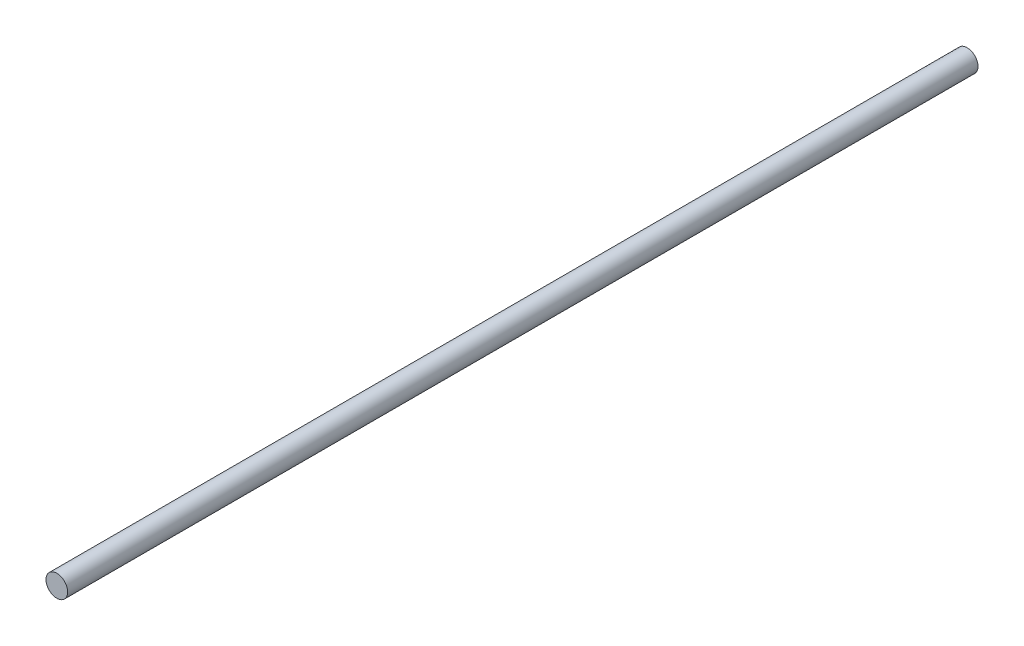
SolidWorks part; units mm, degrees
ref_plane "Спереди" through (0, 0, 0) normal (0, 0, 1) x (1, 0, 0)
ref_plane "Сверху" through (0, 0, 0) normal (0, 1, 0) x (1, 0, 0)
ref_plane "Справа" through (0, 0, 0) normal (1, 0, 0) x (0, 0, -1)
sketch "Эскиз1" plane through (0, 0, 0) normal (0, 0, 1) x (1, 0, 0)
  circle A0 centre (0, 0) radius 6
  dimension "D1" = 12
extrude "Бобышка-Вытянуть1" add sketch "Эскиз1" against normal blind 504
